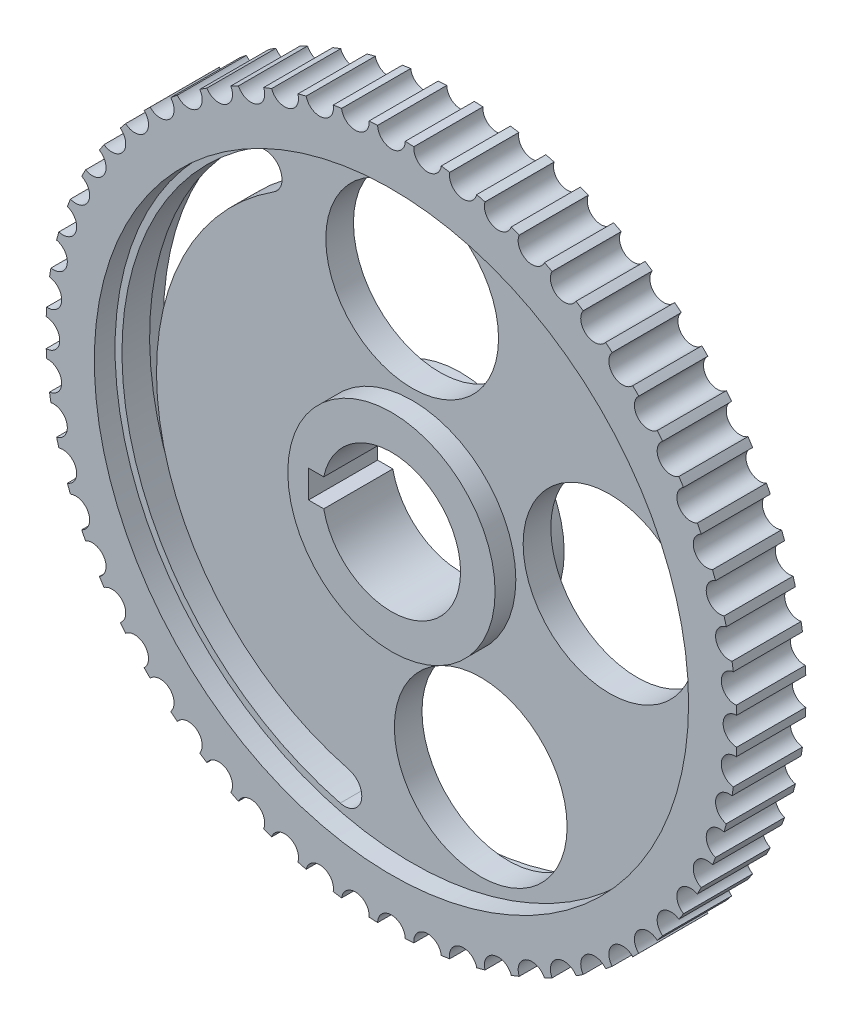
SolidWorks part; units mm, degrees
ref_plane "前视基准面" through (0, 0, 0) normal (0, 0, 1) x (1, 0, 0)
ref_plane "上视基准面" through (0, 0, 0) normal (0, 1, 0) x (1, 0, 0)
ref_plane "右视基准面" through (0, 0, 0) normal (1, 0, 0) x (0, 0, -1)
sketch "Sketch1" plane through (0, 0, 0) normal (0, 0, 1) x (1, 0, 0)
  circle A0 centre (0, 0) radius 50
extrude "Boss-Extrude1" add sketch "Sketch1" along normal blind 10
sketch "Sketch2" plane through (0, 0, 10) normal (0, 0, 1) x (1, 0, 0)
  circle A0 centre (0, 50) radius 2
  circle A1 centre (0, 0) radius 50 construction
  circle A2 centre (5.2264, 49.7261) radius 2
  circle A3 centre (10.3956, 48.9074) radius 2
  circle A4 centre (15.4508, 47.5528) radius 2
  circle A5 centre (20.3368, 45.6773) radius 2
  circle A6 centre (25, 43.3013) radius 2
  circle A7 centre (29.3893, 40.4508) radius 2
  circle A8 centre (33.4565, 37.1572) radius 2
  circle A9 centre (37.1572, 33.4565) radius 2
  circle A10 centre (40.4508, 29.3893) radius 2
  circle A11 centre (43.3013, 25) radius 2
  circle A12 centre (45.6773, 20.3368) radius 2
  circle A13 centre (47.5528, 15.4508) radius 2
  circle A14 centre (48.9074, 10.3956) radius 2
  circle A15 centre (49.7261, 5.2264) radius 2
  circle A16 centre (50, 0) radius 2
  circle A17 centre (49.7261, -5.2264) radius 2
  circle A18 centre (48.9074, -10.3956) radius 2
  circle A19 centre (47.5528, -15.4508) radius 2
  circle A20 centre (45.6773, -20.3368) radius 2
  circle A21 centre (43.3013, -25) radius 2
  circle A22 centre (40.4508, -29.3893) radius 2
  circle A23 centre (37.1572, -33.4565) radius 2
  circle A24 centre (33.4565, -37.1572) radius 2
  circle A25 centre (29.3893, -40.4508) radius 2
  circle A26 centre (25, -43.3013) radius 2
  circle A27 centre (20.3368, -45.6773) radius 2
  circle A28 centre (15.4508, -47.5528) radius 2
  circle A29 centre (10.3956, -48.9074) radius 2
  circle A30 centre (5.2264, -49.7261) radius 2
  circle A31 centre (0, -50) radius 2
  circle A32 centre (-5.2264, -49.7261) radius 2
  circle A33 centre (-10.3956, -48.9074) radius 2
  circle A34 centre (-15.4508, -47.5528) radius 2
  circle A35 centre (-20.3368, -45.6773) radius 2
  circle A36 centre (-25, -43.3013) radius 2
  circle A37 centre (-29.3893, -40.4508) radius 2
  circle A38 centre (-33.4565, -37.1572) radius 2
  circle A39 centre (-37.1572, -33.4565) radius 2
  circle A40 centre (-40.4508, -29.3893) radius 2
  circle A41 centre (-43.3013, -25) radius 2
  circle A42 centre (-45.6773, -20.3368) radius 2
  circle A43 centre (-47.5528, -15.4508) radius 2
  circle A44 centre (-48.9074, -10.3956) radius 2
  circle A45 centre (-49.7261, -5.2264) radius 2
  circle A46 centre (-50, 0) radius 2
  circle A47 centre (-49.7261, 5.2264) radius 2
  circle A48 centre (-48.9074, 10.3956) radius 2
  circle A49 centre (-47.5528, 15.4508) radius 2
  circle A50 centre (-45.6773, 20.3368) radius 2
  circle A51 centre (-43.3013, 25) radius 2
  circle A52 centre (-40.4508, 29.3893) radius 2
  circle A53 centre (-37.1572, 33.4565) radius 2
  circle A54 centre (-33.4565, 37.1572) radius 2
  circle A55 centre (-29.3893, 40.4508) radius 2
  circle A56 centre (-25, 43.3013) radius 2
  circle A57 centre (-20.3368, 45.6773) radius 2
  circle A58 centre (-15.4508, 47.5528) radius 2
  circle A59 centre (-10.3956, 48.9074) radius 2
  circle A60 centre (-5.2264, 49.7261) radius 2
  dimension "D1" = 60
extrude "Cut-Extrude1" cut sketch "Sketch2" against normal blind 10
sketch "Sketch3" plane through (0, 0, 10) normal (0, 0, 1) x (1, 0, 0)
  circle A0 centre (0, 0) radius 43
extrude "Cut-Extrude2" cut sketch "Sketch3" against normal blind 3
sketch "Sketch4" plane through (0, 0, 0) normal (0, 0, -1) x (-1, 0, 0)
  circle A0 centre (0, 0) radius 43
extrude "Cut-Extrude3" cut sketch "Sketch4" against normal blind 3
sketch "Sketch7" plane through (0, 0, 7) normal (0, 0, 1) x (1, 0, 0)
  circle A0 centre (0, 0) radius 15
extrude "Boss-Extrude2" add sketch "Sketch7" along normal blind 3
sketch "Sketch8" plane through (0, 0, 3) normal (0, 0, -1) x (-1, 0, 0)
  circle A0 centre (0, 0) radius 15
extrude "Boss-Extrude3" add sketch "Sketch8" along normal blind 3
sketch "Sketch9" plane through (0, 0, 3) normal (0, 0, -1) x (-1, 0, 0)
  line L0 (0, 43) -> (0, 15) construction
  line L1 (0, 0) -> (0, 29) construction
  line L2 (0, 0) -> (-28.5594, 5.0358) construction
  circle A0 centre (0, 0) radius 43 construction
  circle A1 centre (0, 0) radius 43 construction
  circle A2 centre (0, 0) radius 15 construction
  circle A3 centre (0, 29) radius 12.5
  circle A4 centre (-28.5594, 5.0358) radius 12.5
  circle A5 centre (-9.9186, -27.2511) radius 12.5
  dimension "D1" = 3
  dimension "D2" = 80
extrude "Cut-Extrude4" cut sketch "Sketch9" against normal blind 5
sketch "Sketch10" plane through (0, 0, 3) normal (0, 0, -1) x (-1, 0, 0)
  circle A0 centre (0, 0) radius 39.5 construction
  arc A1 (21.3384, 33.2404) -> (9.7925, -38.2669) centre (0, 0) cw
  arc A2 (19.9878, 31.1366) -> (9.1727, -35.845) centre (0, 0) cw
  arc A3 (22.6889, 35.3442) -> (10.4123, -40.6889) centre (0, 0) cw
  arc A4 (22.6889, 35.3442) -> (19.9878, 31.1366) centre (21.3384, 33.2404) ccw
  arc A5 (9.1727, -35.845) -> (10.4123, -40.6889) centre (9.7925, -38.2669) ccw
  dimension "D1" = 2.5
  dimension "D2" = 2.5
extrude "Cut-Extrude5" cut sketch "Sketch10" against normal blind 5
sketch "Sketch11" plane through (0, 0, 0) normal (0, 0, -1) x (-1, 0, 0)
  line L1 (8, 2) -> (12, 2)
  line L2 (8, 2) -> (8, -2)
  line L3 (8, -2) -> (12, -2)
  line L4 (12, 2) -> (12, -2)
  line L5 (8, 2) -> (12, -2) construction
  line L6 (8, -2) -> (12, 2) construction
  circle A0 centre (0, 0) radius 10
  point P2 (10, 0)
  dimension "D1" = 4
  dimension "D2" = 4
extrude "Cut-Extrude7" cut sketch "Sketch11" against normal blind 10 contours L1 A0 L3 L2 | A0 L3 L4 L1 | L3 A0 L1 L2
